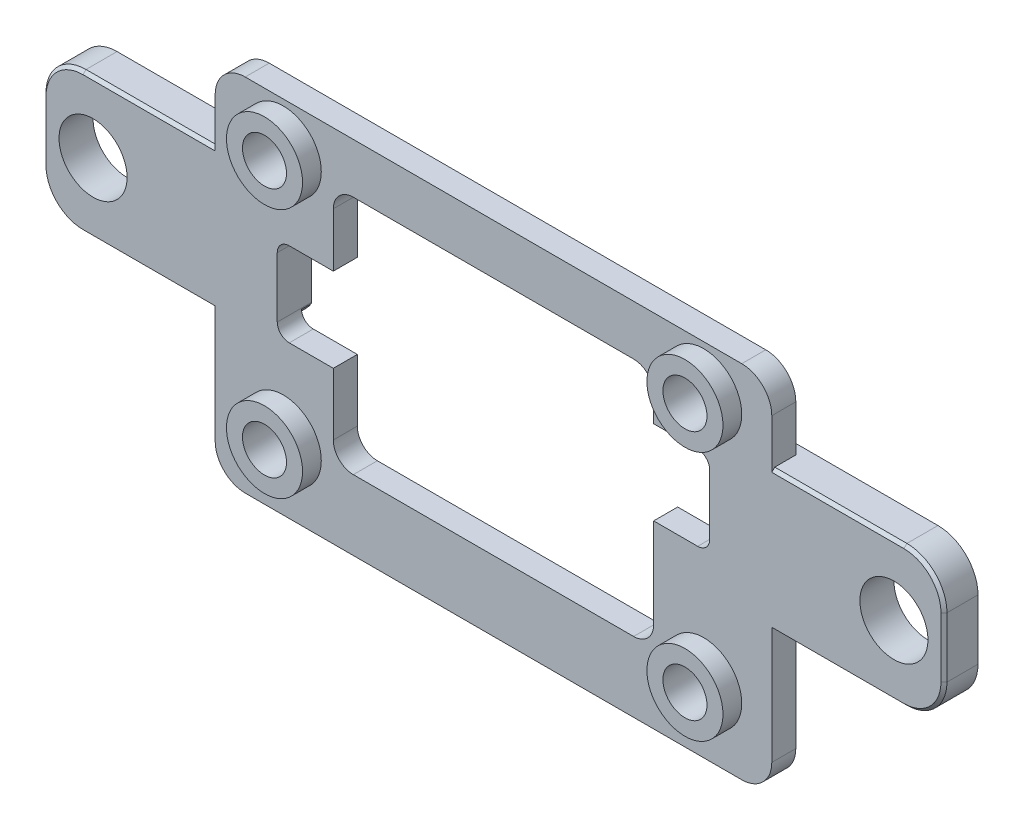
SolidWorks part; units mm, degrees
ref_plane "前视基准面" through (0, 0, 0) normal (0, 0, 1) x (1, 0, 0)
ref_plane "上视基准面" through (0, 0, 0) normal (0, 1, 0) x (1, 0, 0)
ref_plane "右视基准面" through (0, 0, 0) normal (1, 0, 0) x (0, 0, -1)
other "Configuration Table"
sketch "圆角开框绝缘托板" plane through (0, 0, 0) normal (0, 0, 1) x (1, 0, 0)
  line L0 (-12.4, -15.7) -> (12.4, -15.7)
  line L1 (13.9, -14.2) -> (13.9, 0.8)
  line L2 (12.4, 2.3) -> (-12.4, 2.3)
  line L3 (-13.9, 0.8) -> (-13.9, -14.2)
  line L4 (-7, -12.2) -> (7, -12.2)
  line L5 (8, -11.2) -> (8, -1.2)
  line L6 (7, -0.2) -> (-7, -0.2)
  line L7 (-8, -1.2) -> (-8, -11.2)
  arc A0 (12.4, -15.7) -> (13.9, -14.2) centre (12.4, -14.2) ccw
  arc A1 (13.9, 0.8) -> (12.4, 2.3) centre (12.4, 0.8) ccw
  arc A2 (-12.4, 2.3) -> (-13.9, 0.8) centre (-12.4, 0.8) ccw
  arc A3 (-13.9, -14.2) -> (-12.4, -15.7) centre (-12.4, -14.2) ccw
  arc A4 (7, -12.2) -> (8, -11.2) centre (7, -11.2) ccw
  arc A5 (8, -1.2) -> (7, -0.2) centre (7, -1.2) ccw
  arc A6 (-7, -0.2) -> (-8, -1.2) centre (-7, -1.2) ccw
  arc A7 (-8, -11.2) -> (-7, -12.2) centre (-7, -11.2) ccw
  dimension "D1" = 1.5
  dimension "D2" = 1
  dimension "D3" = 5.9
  dimension "D4" = 21.9
  dimension "D5" = 27.8
  dimension "D6" = 2.5
  dimension "D7" = 14.5
  dimension "D8" = 18
extrude "托板抬高0_5并厚1_2" add sketch "圆角开框绝缘托板" along normal blind 1.2 from offset 0.5
sketch "双侧下沉安装耳" plane through (0, 0, 0) normal (0, 0, 1) x (1, 0, 0)
  line L0 (-20.5, -8.5) -> (-12.5, -8.5)
  line L1 (-10.5, -6.5) -> (-10.5, -3.5)
  line L2 (-12.5, -1.5) -> (-20.5, -1.5)
  line L3 (-22.5, -3.5) -> (-22.5, -6.5)
  line L4 (12.5, -8.5) -> (20.5, -8.5)
  line L5 (22.5, -6.5) -> (22.5, -3.5)
  line L6 (20.5, -1.5) -> (12.5, -1.5)
  line L7 (10.5, -3.5) -> (10.5, -6.5)
  arc A0 (-12.5, -8.5) -> (-10.5, -6.5) centre (-12.5, -6.5) ccw
  arc A1 (-10.5, -3.5) -> (-12.5, -1.5) centre (-12.5, -3.5) ccw
  arc A2 (-20.5, -1.5) -> (-22.5, -3.5) centre (-20.5, -3.5) ccw
  arc A3 (-22.5, -6.5) -> (-20.5, -8.5) centre (-20.5, -6.5) ccw
  arc A4 (20.5, -8.5) -> (22.5, -6.5) centre (20.5, -6.5) ccw
  arc A5 (22.5, -3.5) -> (20.5, -1.5) centre (20.5, -3.5) ccw
  arc A6 (12.5, -1.5) -> (10.5, -3.5) centre (12.5, -3.5) ccw
  arc A7 (10.5, -6.5) -> (12.5, -8.5) centre (12.5, -6.5) ccw
  dimension "D1" = 2
  dimension "D2" = 12
  dimension "D3" = 33
  dimension "D4" = 7
extrude "安装耳底面基准与厚1_7" add sketch "双侧下沉安装耳" along normal blind 1.7
sketch "四点绝缘支承柱" plane through (0, 0, 0) normal (0, 0, 1) x (1, 0, 0)
  circle A0 centre (-10.5, -12.4) radius 1.9
  circle A1 centre (-10.5, 0.1) radius 1.9
  circle A2 centre (10.5, -12.4) radius 1.9
  circle A3 centre (10.5, 0.1) radius 1.9
  dimension "D1" = 3.8
  dimension "D2" = 21
  dimension "D3" = 12.5
extrude "官方模型板背支承高度" add sketch "四点绝缘支承柱" along normal blind 0.9373 from offset 1.7
sketch "四个相机M2间隙孔" plane through (0, 0, 0) normal (0, 0, 1) x (1, 0, 0)
  circle A0 centre (-10.5, -12.4) radius 1.1
  circle A1 centre (-10.5, 0.1) radius 1.1
  circle A2 centre (10.5, -12.4) radius 1.1
  circle A3 centre (10.5, 0.1) radius 1.1
  dimension "D1" = 2.2
  dimension "D2" = 21
  dimension "D3" = 12.5
extrude "相机紧固通孔" cut sketch "四个相机M2间隙孔" along normal through all
sketch "双耳M3间隙孔" plane through (0, 0, 0) normal (0, 0, 1) x (1, 0, 0)
  circle A0 centre (-20, -5) radius 1.7
  circle A1 centre (20, -5) radius 1.7
  dimension "D1" = 3.4
  dimension "D2" = 40
extrude "托架连接通孔" cut sketch "双耳M3间隙孔" along normal through all
sketch "板背双器件圆角避空" plane through (0, 0, 0) normal (0, 0, 1) x (1, 0, 0)
  line L0 (7.2, -6.7) -> (10.2, -6.7)
  line L1 (10.8, -6.1) -> (10.8, -3.1)
  line L2 (10.2, -2.5) -> (7.2, -2.5)
  line L3 (6.6, -3.1) -> (6.6, -6.1)
  line L4 (-10.2, -8.1) -> (-7.2, -8.1)
  line L5 (-6.6, -7.5) -> (-6.6, -4.5)
  line L6 (-7.2, -3.9) -> (-10.2, -3.9)
  line L7 (-10.8, -4.5) -> (-10.8, -7.5)
  arc A0 (10.2, -6.7) -> (10.8, -6.1) centre (10.2, -6.1) ccw
  arc A1 (10.8, -3.1) -> (10.2, -2.5) centre (10.2, -3.1) ccw
  arc A2 (7.2, -2.5) -> (6.6, -3.1) centre (7.2, -3.1) ccw
  arc A3 (6.6, -6.1) -> (7.2, -6.7) centre (7.2, -6.1) ccw
  arc A4 (-7.2, -8.1) -> (-6.6, -7.5) centre (-7.2, -7.5) ccw
  arc A5 (-6.6, -4.5) -> (-7.2, -3.9) centre (-7.2, -4.5) ccw
  arc A6 (-10.2, -3.9) -> (-10.8, -4.5) centre (-10.2, -4.5) ccw
  arc A7 (-10.8, -7.5) -> (-10.2, -8.1) centre (-10.2, -7.5) ccw
  dimension "D1" = 0.6
  dimension "D2" = 4.2
  dimension "D3" = 17.4
  dimension "D4" = 1.4
extrude "板背器件维护避空贯通" cut sketch "板背双器件圆角避空" along normal through all
chamfer "安装耳外缘去锐C0_15" distance 0.15 angle 45 6 edges at (21.9142, -2.0858, 1.7) (22.5, -5, 1.7) (21.9142, -7.9142, 1.7) (-21.9142, -7.9142, 1.7) (-21.9142, -2.0858, 1.7) (-22.5, -5, 1.7)
